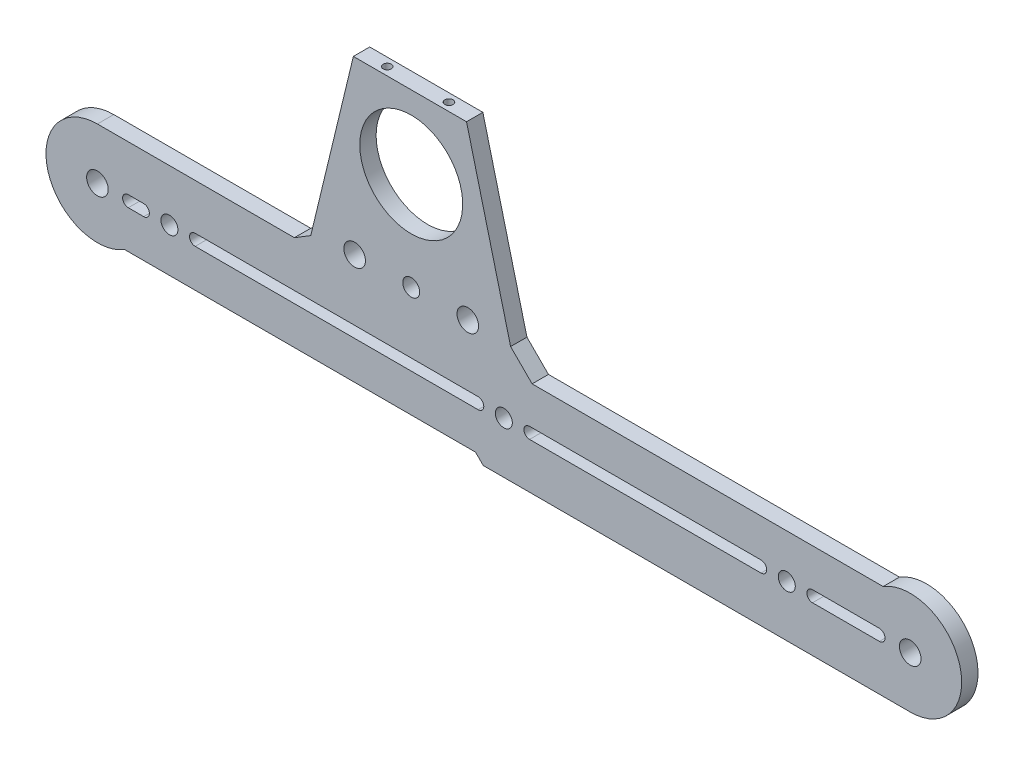
SolidWorks part; units mm, degrees
ref_plane "Front Plane" through (0, 0, 0) normal (0, 0, 1) x (1, 0, 0)
ref_plane "Top Plane" through (0, 0, 0) normal (0, 1, 0) x (1, 0, 0)
ref_plane "Right Plane" through (0, 0, 0) normal (1, 0, 0) x (0, 0, -1)
sketch "Sketch1" plane through (0, 0, 0) normal (0, 0, 1) x (1, 0, 0)
  line L1 (-79, 10) -> (79, 10)
  line L2 (-79, 10) -> (-79, -10) construction
  line L3 (-79, -10) -> (79, -10)
  line L4 (79, 10) -> (79, -10) construction
  line L5 (0, -10) -> (0, 10) construction
  line L6 (-79, 0) -> (79, 0) construction
  arc A0 (-79, -10) -> (-79, 10) centre (-79, 0) cw
  arc A1 (79, 10) -> (79, -10) centre (79, 0) cw
  point P0 (0, 0)
  dimension "D1" = 158
  dimension "D2" = 20
extrude "Boss-Extrude1" add sketch "Sketch1" along normal blind 3.175
hole_wizard "Tap Drill for M5x0.8 Tap1" positions "Sketch5" profile "Sketch6" hole size "M5x0.8" standard "ANSI Metric" end condition through all
sketch "Sketch5" plane through (0, 0, 0) normal (0, 0, -1) x (-1, 0, 0)
  point P0 (-79, 0)
  point P3 (79, 0)
sketch "Sketch6" plane through (79, 0, 0) normal (1, 0, 0) x (0, 1, 0)
  line L0 (0, 0) -> (0, 3.175)
  line L1 (0, 3.175) -> (2.1, 3.175)
  line L2 (2.1, 3.175) -> (2.1, 0)
  line L5 (2.1, 0) -> (0, 0)
  line L11 (0, -6.35) -> (0, 107.95) construction
  dimension "Thru Hole Dia." = 4.2
  dimension "Thru Hole Depth" = 3.175
sketch "Sketch7" plane through (0, 0, 0) normal (0, 0, -1) x (-1, 0, 0)
  line L0 (-79, 6.5) -> (7, 6.5) construction
  line L1 (7, 13) -> (29, 13) construction
  line L2 (18, 13) -> (18, 32) construction
  line L4 (-17.25, 46.25) -> (29.25, 46.25)
  line L5 (-17.25, 46.25) -> (-17.25, 17.75)
  line L6 (-17.25, 17.75) -> (29.25, 17.75)
  line L7 (29.25, 46.25) -> (29.25, 17.75)
  line L8 (6, 17.75) -> (6, 46.25) construction
  line L9 (-17.25, 32) -> (29.25, 32) construction
  circle A0 centre (18, 32) radius 12.5
  circle A1 centre (7, 13) radius 7.5
  circle A2 centre (-79, 0) radius 6.5
  circle A3 centre (7, 13) radius 6.5
  circle A4 centre (29, 13) radius 7.5
  circle A5 centre (29, 13) radius 6.5
  circle A6 centre (7, 13) radius 3.5
  point P44 (6, 32)
  dimension "D1" = 25
  dimension "D2" = 15
  dimension "D3" = 13
  dimension "D9" = 7
  dimension "D4" = 18
  dimension "D5" = 32
  dimension "D6" = 11.25
  dimension "D7" = 46.5
  dimension "D8" = 28.5
  dimension "D10" = 22
sketch "Sketch8" plane through (0, 0, 0) normal (0, 0, -1) x (-1, 0, 0)
  line L13 (0, 99.6228) -> (0, 118.0196) construction
  line L14 (0, 0) -> (0, 46.25) construction
  line L15 (29.25, 46.25) -> (7.25, 46.25)
  line L16 (7.25, 46.25) -> (-2, 10)
  line L17 (-79, 10) -> (79, 10) construction
  line L18 (-2, 10) -> (38, 10)
  line L19 (38, 10) -> (29.25, 46.25)
  line L20 (-17.25, 46.25) -> (29.25, 46.25) construction
  line L21 (18, 32) -> (18, 10) construction
  dimension "D1" = 22
  dimension "D2" = 40
extrude "Boss-Extrude2" add sketch "Sketch8" against normal up to surface (3.175 mm away) up to face at (76.9, 0, 3.175)
hole_wizard "Tap Drill for M5x0.8 Tap2" positions "Sketch9" profile "Sketch10" hole size "M5x0.8" standard "ANSI Metric" end condition through all
sketch "Sketch9" plane through (0, 0, 0) normal (0, 0, -1) x (-1, 0, 0)
  point P0 (7, 13)
  point P3 (29, 13)
sketch "Sketch10" plane through (-7, 13, 0) normal (1, 0, 0) x (0, 1, 0)
  line L0 (0, 0) -> (0, 3.175)
  line L1 (0, 3.175) -> (2.1, 3.175)
  line L2 (2.1, 3.175) -> (2.1, 0)
  line L5 (2.1, 0) -> (0, 0)
  line L11 (0, -6.35) -> (0, 107.95) construction
  dimension "Thru Hole Dia." = 4.2
  dimension "Thru Hole Depth" = 3.175
sketch "Sketch11" plane through (0, 0, 0) normal (0, 0, -1) x (-1, 0, 0)
  circle A0 centre (18, 32) radius 10
  dimension "D1" = 20
extrude "Cut-Extrude3" cut sketch "Sketch11" against normal up to surface (3.175 mm away) up to face at (-9.1, 13, 3.175)
hole_wizard "Tap Drill for M4x0.7 Tap1" positions "Sketch14" profile "Sketch15" hole size "M4x0.7" standard "ANSI Metric" end condition through all
sketch "Sketch14" plane through (0, 0, 0) normal (0, 0, -1) x (-1, 0, 0)
  line L0 (0, 0) -> (-55, 0) construction
  line L2 (0, 0) -> (65, 0) construction
  point P5 (-55, 0)
  point P14 (18, 13)
  point P22 (65, 0)
  point P32 (0, 0)
  dimension "D2" = 55
  dimension "D3" = 65
sketch "Sketch15" plane through (0, 0, 0) normal (1, 0, 0) x (0, 1, 0)
  line L0 (0, 0) -> (0, 3.175)
  line L1 (0, 3.175) -> (1.65, 3.175)
  line L2 (1.65, 3.175) -> (1.65, 0)
  line L5 (1.65, 0) -> (0, 0)
  line L11 (0, -6.35) -> (0, 107.95) construction
  dimension "Thru Hole Dia." = 3.3
  dimension "Thru Hole Depth" = 3.175
sketch "Sketch16" plane through (0, 0, 0) normal (0, 0, -1) x (-1, 0, 0)
  line L0 (0, 0) -> (26.7225, 0) construction
  line L1 (-73, 0) -> (-60, 0) construction
  line L2 (-73, 2) -> (-60, 2)
  line L3 (-73, -2) -> (-60, -2)
  line L4 (-50, 0) -> (-5, 0) construction
  line L5 (-50, 2) -> (-5, 2)
  line L6 (-50, -2) -> (-5, -2)
  line L7 (5, 0) -> (60, 0) construction
  line L8 (5, 2) -> (60, 2)
  line L9 (5, -2) -> (60, -2)
  line L10 (70, 0) -> (73, 0) construction
  line L11 (70, 2) -> (73, 2)
  line L12 (70, -2) -> (73, -2)
  arc A0 (-73, 2) -> (-73, -2) centre (-73, 0) ccw
  arc A1 (-60, -2) -> (-60, 2) centre (-60, 0) ccw
  arc A2 (-50, 2) -> (-50, -2) centre (-50, 0) ccw
  arc A3 (-5, -2) -> (-5, 2) centre (-5, 0) ccw
  arc A4 (5, 2) -> (5, -2) centre (5, 0) ccw
  arc A5 (60, -2) -> (60, 2) centre (60, 0) ccw
  arc A6 (70, 2) -> (70, -2) centre (70, 0) ccw
  arc A7 (73, -2) -> (73, 2) centre (73, 0) ccw
  point P5 (-66.5, 0)
  point P10 (-27.5, 0)
  point P18 (32.5, 0)
  point P25 (71.5, 0)
  point P32 (79, 0)
  point P33 (-55, 0)
  point P35 (65, 0)
  dimension "D1" = 2
  dimension "D3" = 2
  dimension "D4" = 2
  dimension "D5" = 2
  dimension "D2" = 5
  dimension "D6" = 5
  dimension "D7" = 5
  dimension "D8" = 5
  dimension "D9" = 5
  dimension "D10" = 6
  dimension "D11" = 6
  dimension "D12" = 5
sketch "Sketch17" plane through (0, 0, 0) normal (0, 0, -1) x (-1, 0, 0)
  line L0 (-73, 0) -> (-60, 0) construction
  line L1 (-73, 1.1) -> (-60, 1.1)
  line L2 (-73, -1.1) -> (-60, -1.1)
  line L3 (-50, 0) -> (-5, 0) construction
  line L4 (-50, 1.1) -> (-5, 1.1)
  line L5 (-50, -1.1) -> (-5, -1.1)
  line L6 (5, 0) -> (60, 0) construction
  line L7 (5, 1.1) -> (60, 1.1)
  line L8 (5, -1.1) -> (60, -1.1)
  line L9 (70, 0) -> (73, 0) construction
  line L10 (70, 1.1) -> (73, 1.1)
  line L11 (70, -1.1) -> (73, -1.1)
  arc A0 (-73, 1.1) -> (-73, -1.1) centre (-73, 0) ccw
  arc A1 (-60, -1.1) -> (-60, 1.1) centre (-60, 0) ccw
  arc A2 (-50, 1.1) -> (-50, -1.1) centre (-50, 0) ccw
  arc A3 (-5, -1.1) -> (-5, 1.1) centre (-5, 0) ccw
  arc A4 (5, 1.1) -> (5, -1.1) centre (5, 0) ccw
  arc A5 (60, -1.1) -> (60, 1.1) centre (60, 0) ccw
  arc A6 (70, 1.1) -> (70, -1.1) centre (70, 0) ccw
  arc A7 (73, -1.1) -> (73, 1.1) centre (73, 0) ccw
  point P4 (-66.5, 0)
  point P9 (-27.5, 0)
  point P18 (32.5, 0)
  point P27 (71.5, 0)
  dimension "D1" = 1.1
  dimension "D2" = 1.1
  dimension "D3" = 1.1
  dimension "D4" = 1.1
extrude "Cut-Extrude5" cut sketch "Sketch17" against normal up to surface (3.175 mm away) up to face at (53.35, 0, 3.175)
chamfer "Chamfer1" distance 2 angle 45 2 edges at (2, 10, 1.5875) (-38, 10, 1.5875)
sketch "Sketch18" plane through (0, 0, 3.175) normal (0, 0, 1) x (1, 0, 0)
  line L0 (4, 10) -> (5.5, 8.5)
  line L1 (5.5, 8.5) -> (73.7322, 8.5)
  line L2 (4, 10) -> (79, 10)
  line L3 (4, 10) -> (1.3148, 12.6852) construction
  line L4 (-4, -10) -> (-79, -10)
  line L5 (-5.5, -8.5) -> (-73.7322, -8.5)
  line L6 (-4, -10) -> (-5.5, -8.5)
  arc A0 (73.7322, 8.5) -> (79, 10) centre (79, 0) cw
  arc A1 (79, -10) -> (79, 10) centre (79, 0) ccw construction
  arc A2 (-73.7322, -8.5) -> (-79, -10) centre (-79, 0) cw
  point P19 (0, 0)
  dimension "D1" = 8.5
  dimension "D2" = 2
extrude "Cut-Extrude6" cut sketch "Sketch18" against normal blind 9
hole_wizard "Tap Drill for M2x0.4 Tap1" positions "Sketch19" profile "Sketch20" hole size "M2x0.4" standard "ANSI Metric"
sketch "Sketch19" plane through (0, 46.25, 0) normal (0, 1, 0) x (1, 0, 0)
  line L0 (-18.25, 0) -> (-18.25, -3.175) construction
  line L1 (-29.25, 0) -> (-7.25, 0) construction
  line L2 (-7.25, -3.175) -> (-29.25, -3.175) construction
  line L4 (-18.25, -1.5875) -> (-12.25, -1.5875) construction
  point P10 (-12.25, -1.5875)
  point P17 (-24.25, -1.5875)
  dimension "D1" = 6
sketch "Sketch20" plane through (-24.25, 46.25, 1.5875) normal (1, 0, 0) x (0, 0, 1)
  line L0 (0, 0) -> (0, 3.4807)
  line L1 (0, 3.4807) -> (0.8, 3)
  line L2 (0.8, 3) -> (0.8, 0)
  line L5 (0.8, 0) -> (0, 0)
  line L10 (0, 3.4807) -> (-0.8, 3) construction
  line L11 (0, -6.35) -> (0, 107.95) construction
  dimension "Hole Dia." = 1.6
  dimension "Hole Depth" = 3
  dimension "Drill Angle" = 118
